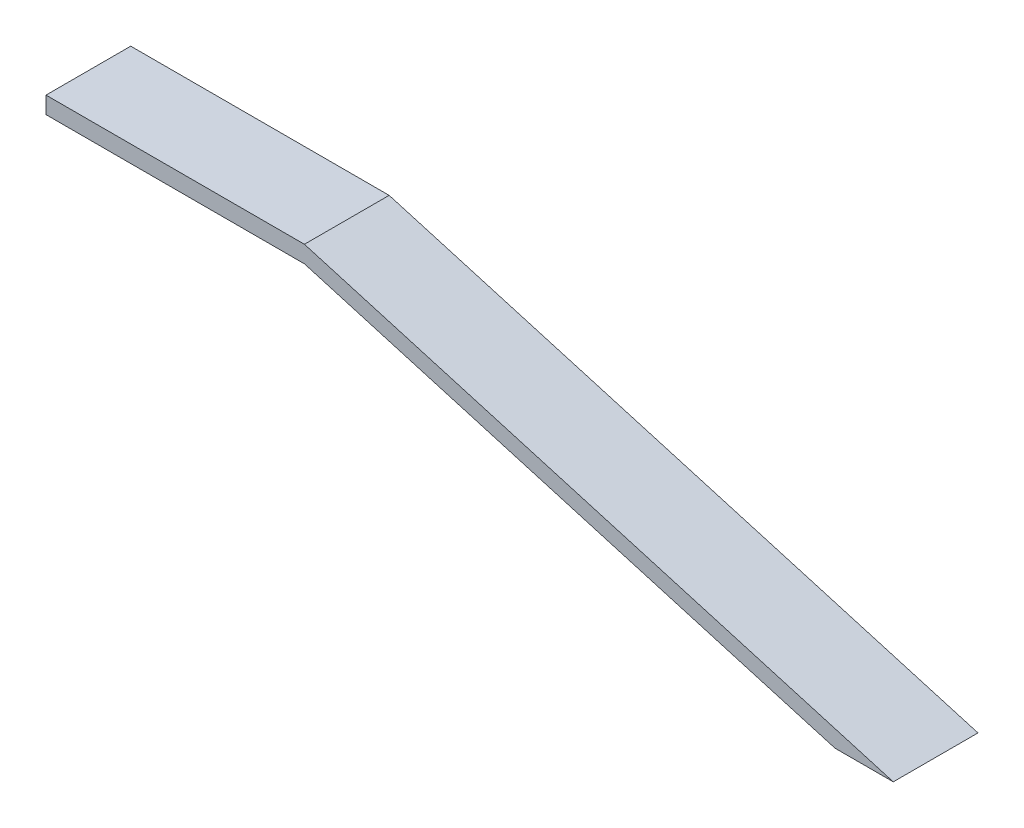
SolidWorks part; units mm, degrees
ref_plane "Front Plane" through (0, 0, 0) normal (0, 0, 1) x (1, 0, 0)
ref_plane "Top Plane" through (0, 0, 0) normal (0, 1, 0) x (1, 0, 0)
ref_plane "Right Plane" through (0, 0, 0) normal (1, 0, 0) x (0, 0, -1)
sketch "Sketch1" plane through (0, 0, 0) normal (0, 0, 1) x (1, 0, 0)
  line L1 (127, 88.9) -> (-127, 88.9)
  line L2 (127, 88.9) -> (127, -88.9)
  line L3 (127, -88.9) -> (-127, -88.9)
  line L4 (-127, 88.9) -> (-127, -88.9)
  line L5 (127, 88.9) -> (-127, -88.9) construction
  line L6 (127, -88.9) -> (-127, 88.9) construction
  point P0 (0, 0)
  dimension "D1" = 177.8
  dimension "D2" = 254
extrude "Boss-Extrude1" add sketch "Sketch1" along normal blind 25.4
sketch "Sketch3" plane through (0, 0, 25.4) normal (0, 0, 1) x (1, 0, 0)
  line L0 (-127, 88.9) -> (-49.53, 88.9)
  line L1 (-127, 88.9) -> (-127, -88.9) construction
  line L3 (127, 88.9) -> (-127, 88.9) construction
  line L4 (-127, 88.9) -> (-127, 37.598) construction
  line L5 (-127, 88.9) -> (-127, 83.82)
  line L7 (-127, 37.598) -> (127, 37.598) construction
  line L10 (127, -88.9) -> (127, 88.9) construction
  line L11 (-49.53, 88.9) -> (127, 37.598)
  line L13 (-127, 83.82) -> (-49.53, 83.82)
  line L16 (-49.53, 83.82) -> (109.5197, 37.598)
  line L17 (127, 37.598) -> (109.5197, 37.598)
  dimension "D1" = 77.47
extrude "Cut-Extrude1" cut sketch "Sketch3" against normal through all
